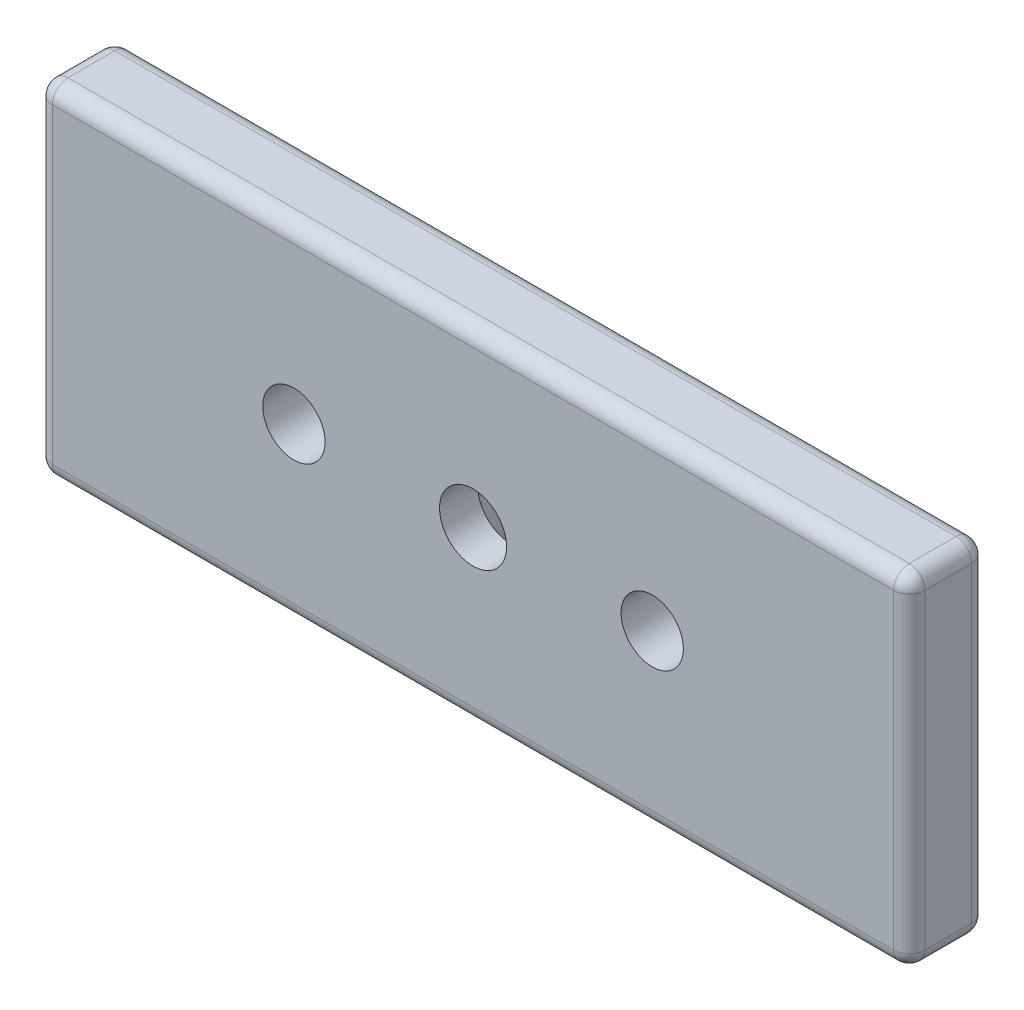
SolidWorks part; units mm, degrees
ref_plane "Front Plane" through (0, 0, 0) normal (0, 0, 1) x (1, 0, 0)
ref_plane "Top Plane" through (0, 0, 0) normal (0, 1, 0) x (1, 0, 0)
ref_plane "Right Plane" through (0, 0, 0) normal (1, 0, 0) x (0, 0, -1)
sketch "Sketch-Base" plane through (0, 0, 0) normal (0, 0, 1) x (1, 0, 0)
  line L1 (0, 0) -> (56, 0)
  line L2 (0, 0) -> (0, 22)
  line L3 (0, 22) -> (56, 22)
  line L4 (56, 0) -> (56, 22)
  dimension "D1" = 56
  dimension "D2" = 22
extrude "Base-Extrude" add sketch "Sketch-Base" along normal blind 5
sketch "Sketch2" plane through (0, 0, 5) normal (0, 0, 1) x (1, 0, 0)
  line L0 (0, 0) -> (56, 0) construction
  line L1 (0, 22) -> (0, 0) construction
  circle A1 centre (16.5, 11) radius 2
  circle A2 centre (39.5, 11) radius 2
  dimension "D1" = 4
  dimension "D2" = 11
  dimension "D3" = 16.5
  dimension "D4" = 39.5
extrude "Mounting Holes" cut sketch "Sketch2" against normal through all
fillet "Small Edge Fillet" radius 1 4 edges at (56, 22, 2.5) (56, 0, 2.5) (0, 0, 2.5) (0, 22, 2.5)
fillet "Fillet4" radius 1 16 edges at (55.7071, 21.7071, 0) (56, 11, 0) (55.7071, 0.2929, 0) (28, 0, 0) (0.2929, 0.2929, 0) (0, 11, 0) (0.2929, 21.7071, 0) (55.7071, 21.7071, 5) (56, 11, 5) (55.7071, 0.2929, 5) (28, 0, 5) (0.2929, 0.2929, 5) (0, 11, 5) (0.2929, 21.7071, 5) (28, 22, 0) (28, 22, 5)
hole_wizard "CSK for M4 Flat Head Machine Screw4" positions "3DSketch4" profile "Sketch6" countersink size "M4" standard "ANSI Metric" end condition through all
sketch3d "3DSketch4"
  line L0 (1, 1, 0) -> (1, 21, 0) construction
  line L1 (55, 1, 0) -> (1, 1, 0) construction
  point P0 (28, 11, 0)
  dimension "D1" = 27
  dimension "D2" = 10
sketch "Sketch6" plane through (28, 11, 0) normal (1, 0, 0) x (0, 1, 0)
  line L0 (0, 0) -> (0, 5)
  line L1 (0, 5) -> (2.15, 5)
  line L2 (2.15, 5) -> (2.15, 2.55)
  line L3 (2.15, 2.55) -> (4.7, 0)
  line L5 (4.7, 0) -> (0, 0)
  line L6 (-2.15, 2.55) -> (-4.7, 0) construction
  line L11 (0, -6.35) -> (0, 107.95) construction
  dimension "Thru Hole Dia." = 4.3
  dimension "Thru Hole Depth" = 5
  dimension "Near C'Sink Dia." = 9.4
  dimension "Near C'Sink Angle" = 90
